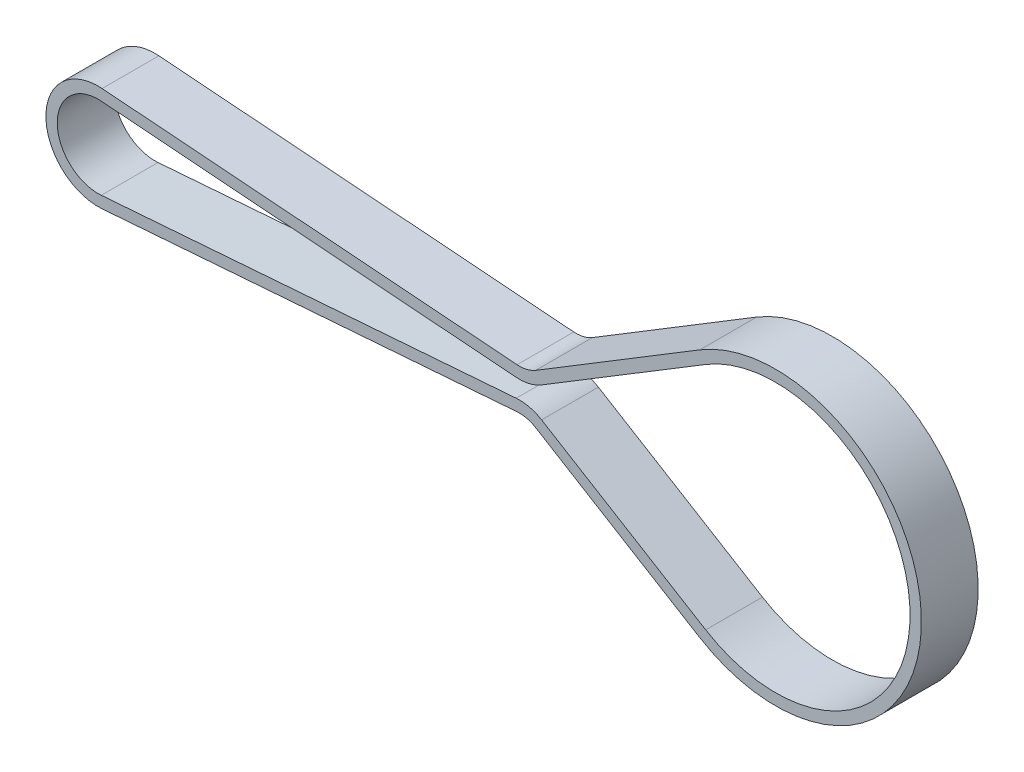
SolidWorks part; units mm, degrees
ref_plane "Front Plane" through (0, 0, 0) normal (0, 0, 1) x (1, 0, 0)
ref_plane "Top Plane" through (0, 0, 0) normal (0, 1, 0) x (1, 0, 0)
ref_plane "Right Plane" through (0, 0, 0) normal (1, 0, 0) x (0, 0, -1)
sketch "Sketch2" plane through (0, 0, 0) normal (0, 0, 1) x (1, 0, 0)
  line L0 (0, 0) -> (1, 0) construction
  line L1 (0, 0) -> (0, 1) construction
  line L2 (0.7719, 10.0955) -> (81.1787, 3.9479)
  line L3 (84.7954, 4.814) -> (116.5893, 24.1497)
  line L4 (116.5892, -24.1496) -> (84.7955, -4.8138)
  line L5 (81.1786, -3.9477) -> (0.7719, -10.0955)
  arc A0 (0.7719, -10.0955) -> (0.7719, 10.0955) centre (0, 0) cw
  arc A1 (81.1787, 3.9479) -> (84.7954, 4.814) centre (81.6414, 10.0002) ccw
  arc A2 (116.5893, 24.1497) -> (116.5892, -24.1496) centre (131.2762, 0) cw
  arc A3 (84.7955, -4.8138) -> (81.1786, -3.9477) centre (81.6414, -10) ccw
extrude "Extrude-Thin1" add sketch "Sketch2" along normal up to surface (5.5 mm away) and the other way up to surface (5.5 mm away) thin
